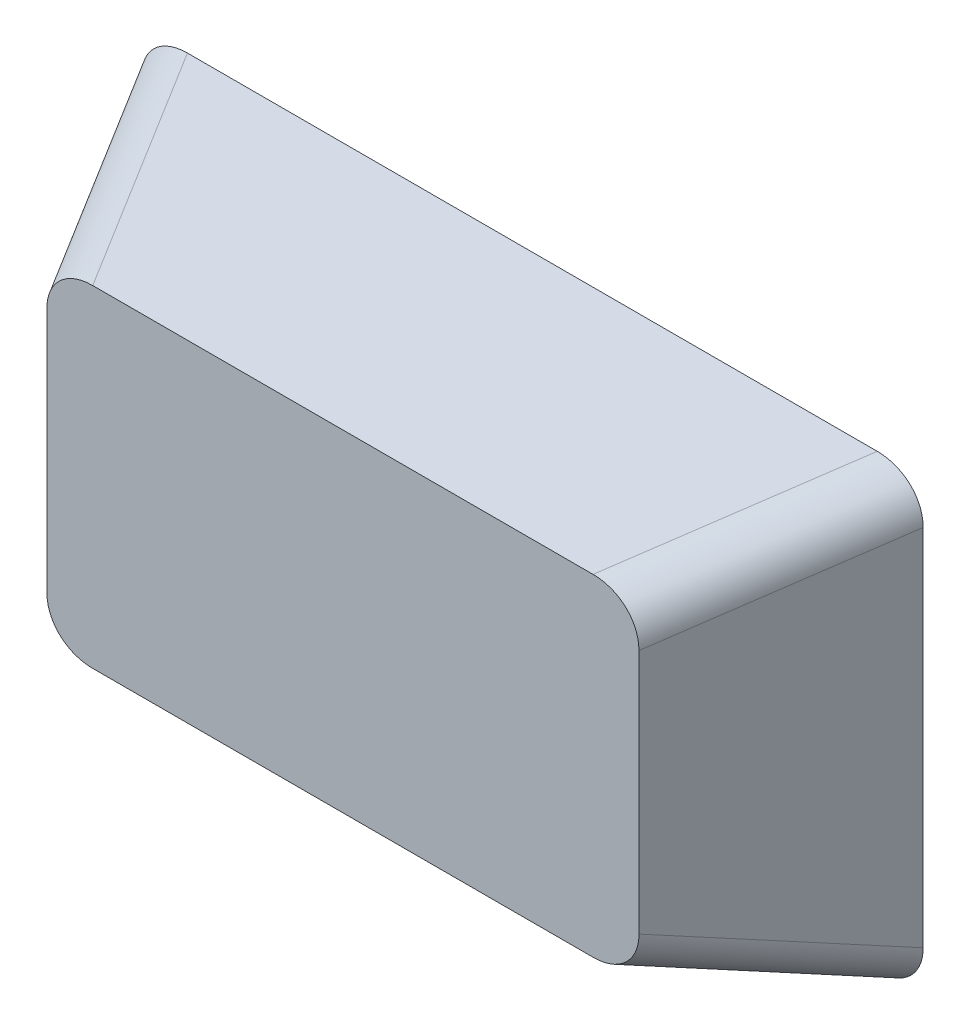
SolidWorks part; units mm, degrees
ref_plane "Front Plane" through (0, 0, 0) normal (0, 0, 1) x (1, 0, 0)
ref_plane "Top Plane" through (0, 0, 0) normal (0, 1, 0) x (1, 0, 0)
ref_plane "Right Plane" through (0, 0, 0) normal (1, 0, 0) x (0, 0, -1)
sketch "Sketch3" plane through (0, 0, 0) normal (0, 0, 1) x (1, 0, 0)
  line L1 (62.5, -35) -> (-62.5, -35)
  line L2 (62.5, -35) -> (62.5, 35)
  line L3 (62.5, 35) -> (-62.5, 35)
  line L4 (-62.5, -35) -> (-62.5, 35)
  line L5 (62.5, -35) -> (-62.5, 35) construction
  line L6 (62.5, 35) -> (-62.5, -35) construction
  point P0 (0, 0)
  dimension "D1" = 125
  dimension "D2" = 70
ref_plane "Plane1" through (0, 0, -40) normal (0, 0, 1) x (1, 0, 0)
sketch "Sketch4" plane through (0, 0, -40) normal (0, 0, 1) x (1, 0, 0)
  line L1 (82.5, -47.5) -> (-82.5, -47.5)
  line L2 (82.5, -47.5) -> (82.5, 47.5)
  line L3 (82.5, 47.5) -> (-82.5, 47.5)
  line L4 (-82.5, -47.5) -> (-82.5, 47.5)
  line L5 (82.5, -47.5) -> (-82.5, 47.5) construction
  line L6 (82.5, 47.5) -> (-82.5, -47.5) construction
  point P0 (0, 0)
  dimension "D1" = 165
  dimension "D2" = 95
loft "Loft1" add profiles "Sketch3", "Sketch4"
ref_plane "Plane2" through (0, 0, -20) normal (0, 0, 1) x (1, 0, 0)
sketch "Sketch5" plane through (0, 0, -20) normal (0, 0, 1) x (1, 0, 0)
  line L1 (22.5, -12.5) -> (-22.5, -12.5)
  line L2 (22.5, -12.5) -> (22.5, 12.5)
  line L3 (22.5, 12.5) -> (-22.5, 12.5)
  line L4 (-22.5, -12.5) -> (-22.5, 12.5)
  line L5 (22.5, -12.5) -> (-22.5, 12.5) construction
  line L6 (22.5, 12.5) -> (-22.5, -12.5) construction
  point P0 (0, 0)
  dimension "D1" = 45
  dimension "D2" = 25
sketch "Sketch7" plane through (0, 0, -40) normal (0, 0, 1) x (1, 0, 0)
  line L0 (82.5, -47.5) -> (82.5, 47.5) construction
  line L5 (77.5, -42.5) -> (-77.5, -42.5)
  line L6 (77.5, -42.5) -> (77.5, 42.5)
  line L11 (77.5, 42.5) -> (-77.5, 42.5)
  line L12 (-77.5, -42.5) -> (-77.5, 42.5)
  line L13 (77.5, -42.5) -> (-77.5, 42.5) construction
  line L14 (77.5, 42.5) -> (-77.5, -42.5) construction
  line L15 (82.5, 47.5) -> (-82.5, 47.5) construction
  point P0 (0, 0)
  point P1 (0, 0)
  point P7 (0, 0)
  dimension "D1" = 5
  dimension "D2" = 5
loft "Cut-Loft2" cut profiles "Sketch7", "Sketch5"
fillet "Fillet1" radius 10 4 edges
